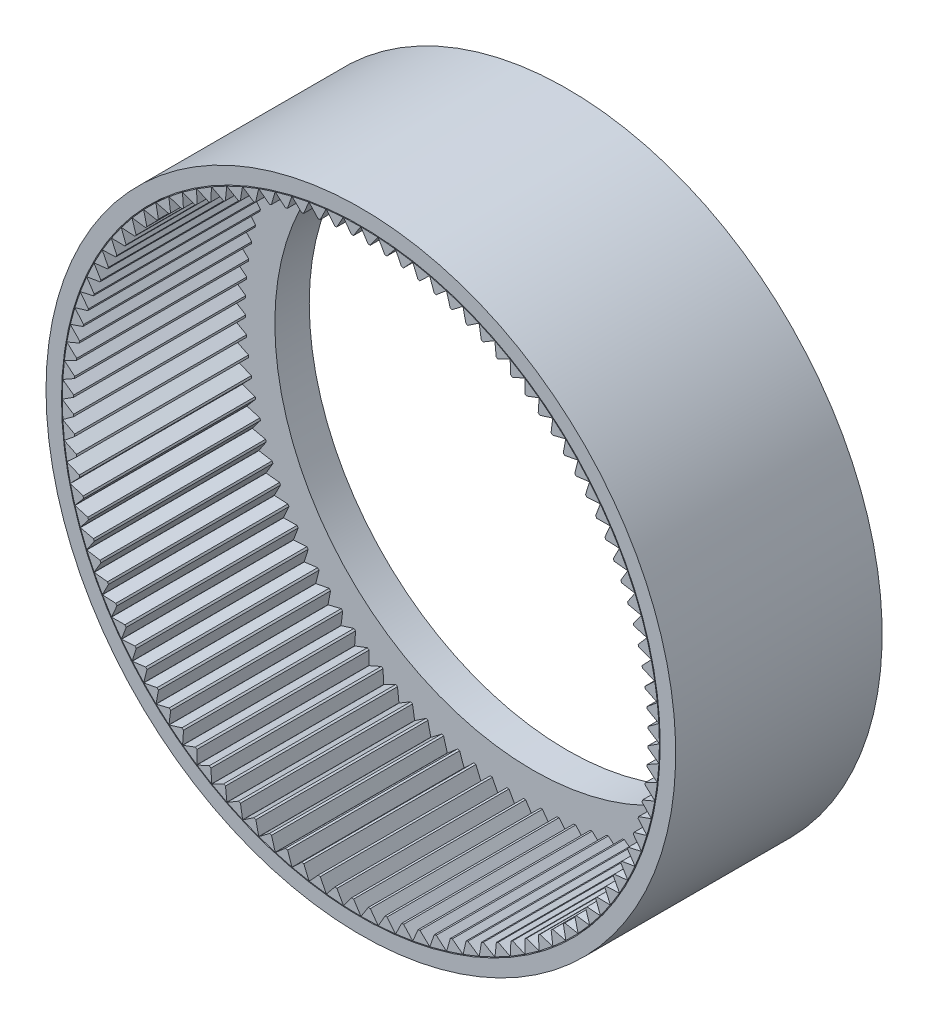
SolidWorks part; units mm, degrees
ref_plane "Alzado" through (0, 0, 0) normal (0, 0, 1) x (1, 0, 0)
ref_plane "Planta" through (0, 0, 0) normal (0, 1, 0) x (1, 0, 0)
ref_plane "Vista lateral" through (0, 0, 0) normal (1, 0, 0) x (0, 0, -1)
sketch "Croquis2" plane through (0, 0, 0) normal (0, 0, 1) x (1, 0, 0)
  line L0 (0, 8.6755) -> (0.2107, 8.3473)
  line L2 (0.5, 8.6611) -> (0.2707, 8.3456)
  line L4 (0.2107, 8.3473) -> (0.2707, 8.3456)
  line L5 (0, 8.6755) -> (0.5, 8.6611)
  line L6 (0.5044, 8.6608) -> (1.0028, 8.6174)
  line L7 (1.0028, 8.6174) -> (0.7555, 8.3158)
  line L8 (0.6957, 8.321) -> (0.7555, 8.3158)
  line L9 (0.5044, 8.6608) -> (0.6957, 8.321)
  line L10 (1.0072, 8.6169) -> (1.5021, 8.5445)
  line L11 (1.5021, 8.5445) -> (1.2378, 8.2578)
  line L12 (1.1784, 8.2664) -> (1.2378, 8.2578)
  line L13 (1.0072, 8.6169) -> (1.1784, 8.2664)
  line L14 (1.5065, 8.5437) -> (1.9964, 8.4427)
  line L15 (1.9964, 8.4427) -> (1.7158, 8.1718)
  line L16 (1.657, 8.1839) -> (1.7158, 8.1718)
  line L17 (1.5065, 8.5437) -> (1.657, 8.1839)
  line L18 (2.0007, 8.4417) -> (2.4839, 8.3123)
  line L19 (2.4839, 8.3123) -> (2.1881, 8.0582)
  line L20 (2.1301, 8.0737) -> (2.1881, 8.0582)
  line L21 (2.0007, 8.4417) -> (2.1301, 8.0737)
  line L22 (2.4882, 8.3111) -> (2.963, 8.1538)
  line L23 (2.963, 8.1538) -> (2.6529, 7.9174)
  line L24 (2.5959, 7.9362) -> (2.6529, 7.9174)
  line L25 (2.4882, 8.3111) -> (2.5959, 7.9362)
  line L26 (2.9672, 8.1523) -> (3.4321, 7.9678)
  line L27 (3.4321, 7.9678) -> (3.1088, 7.7497)
  line L28 (3.053, 7.7719) -> (3.1088, 7.7497)
  line L29 (2.9672, 8.1523) -> (3.053, 7.7719)
  line L30 (3.4362, 7.966) -> (3.8896, 7.7547)
  line L31 (3.8896, 7.7547) -> (3.5541, 7.5558)
  line L32 (3.4997, 7.5812) -> (3.5541, 7.5558)
  line L33 (3.4362, 7.966) -> (3.4997, 7.5812)
  line L34 (3.8936, 7.7527) -> (4.3339, 7.5154)
  line L35 (4.3339, 7.5154) -> (3.9874, 7.3364)
  line L36 (3.9346, 7.3649) -> (3.9874, 7.3364)
  line L37 (3.8936, 7.7527) -> (3.9346, 7.3649)
  line L38 (4.3378, 7.5132) -> (4.7636, 7.2507)
  line L39 (4.7636, 7.2507) -> (4.4073, 7.0922)
  line L40 (4.3562, 7.1237) -> (4.4073, 7.0922)
  line L41 (4.3378, 7.5132) -> (4.3562, 7.1237)
  line L42 (4.7673, 7.2483) -> (5.1771, 6.9615)
  line L43 (5.1771, 6.9615) -> (4.8122, 6.8239)
  line L44 (4.763, 6.8583) -> (4.8122, 6.8239)
  line L45 (4.7673, 7.2483) -> (4.763, 6.8583)
  line L46 (5.1807, 6.9588) -> (5.5731, 6.6487)
  line L47 (5.5731, 6.6487) -> (5.2008, 6.5325)
  line L48 (5.1537, 6.5698) -> (5.2008, 6.5325)
  line L49 (5.1807, 6.9588) -> (5.1537, 6.5698)
  line L50 (5.5765, 6.6458) -> (5.9503, 6.3134)
  line L51 (5.9503, 6.3134) -> (5.5718, 6.2191)
  line L52 (5.527, 6.259) -> (5.5718, 6.2191)
  line L53 (5.5765, 6.6458) -> (5.527, 6.259)
  line L54 (5.9535, 6.3103) -> (6.3073, 5.9567)
  line L55 (6.3073, 5.9567) -> (5.924, 5.8846)
  line L56 (5.8816, 5.927) -> (5.924, 5.8846)
  line L57 (5.9535, 6.3103) -> (5.8816, 5.927)
  line L58 (6.3103, 5.9535) -> (6.643, 5.5799)
  line L59 (6.643, 5.5799) -> (6.2562, 5.5302)
  line L60 (6.2162, 5.575) -> (6.2562, 5.5302)
  line L61 (6.3103, 5.9535) -> (6.2162, 5.575)
  line L62 (6.6458, 5.5765) -> (6.9562, 5.1842)
  line L63 (6.9562, 5.1842) -> (6.5671, 5.1571)
  line L64 (6.5299, 5.2041) -> (6.5671, 5.1571)
  line L65 (6.6458, 5.5765) -> (6.5299, 5.2041)
  line L66 (6.9588, 5.1807) -> (7.2458, 4.771)
  line L67 (7.2458, 4.771) -> (6.8559, 4.7665)
  line L68 (6.8214, 4.8157) -> (6.8559, 4.7665)
  line L69 (6.9588, 5.1807) -> (6.8214, 4.8157)
  line L70 (7.2483, 4.7673) -> (7.511, 4.3416)
  line L71 (7.511, 4.3416) -> (7.1214, 4.3598)
  line L72 (7.0899, 4.4109) -> (7.1214, 4.3598)
  line L73 (7.2483, 4.7673) -> (7.0899, 4.4109)
  line L74 (7.5132, 4.3378) -> (7.7507, 3.8975)
  line L75 (7.7507, 3.8975) -> (7.3629, 3.9384)
  line L76 (7.3344, 3.9912) -> (7.3629, 3.9384)
  line L77 (7.5132, 4.3378) -> (7.3344, 3.9912)
  line L78 (7.7527, 3.8936) -> (7.9642, 3.4403)
  line L79 (7.9642, 3.4403) -> (7.5794, 3.5036)
  line L80 (7.554, 3.558) -> (7.5794, 3.5036)
  line L81 (7.7527, 3.8936) -> (7.554, 3.558)
  line L82 (7.966, 3.4362) -> (8.1508, 2.9714)
  line L83 (8.1508, 2.9714) -> (7.7703, 3.0569)
  line L84 (7.7481, 3.1127) -> (7.7703, 3.0569)
  line L85 (7.966, 3.4362) -> (7.7481, 3.1127)
  line L86 (8.1523, 2.9672) -> (8.3098, 2.4924)
  line L87 (8.3098, 2.4924) -> (7.9349, 2.6)
  line L88 (7.916, 2.6569) -> (7.9349, 2.6)
  line L89 (8.1523, 2.9672) -> (7.916, 2.6569)
  line L90 (8.3111, 2.4882) -> (8.4406, 2.005)
  line L91 (8.4406, 2.005) -> (8.0727, 2.1342)
  line L92 (8.0571, 2.1922) -> (8.0727, 2.1342)
  line L93 (8.3111, 2.4882) -> (8.0571, 2.1922)
  line L94 (8.4417, 2.0007) -> (8.5429, 1.5109)
  line L95 (8.5429, 1.5109) -> (8.1831, 1.6612)
  line L96 (8.1709, 1.72) -> (8.1831, 1.6612)
  line L97 (8.4417, 2.0007) -> (8.1709, 1.72)
  line L98 (8.5437, 1.5065) -> (8.6163, 1.0116)
  line L99 (8.6163, 1.0116) -> (8.2658, 1.1826)
  line L100 (8.2571, 1.242) -> (8.2658, 1.1826)
  line L101 (8.5437, 1.5065) -> (8.2571, 1.242)
  line L102 (8.6169, 1.0072) -> (8.6606, 0.5089)
  line L103 (8.6606, 0.5089) -> (8.3206, 0.7)
  line L104 (8.3154, 0.7598) -> (8.3206, 0.7)
  line L105 (8.6169, 1.0072) -> (8.3154, 0.7598)
  line L106 (8.6608, 0.5044) -> (8.6755, 0.0044)
  line L107 (8.6755, 0.0044) -> (8.3472, 0.215)
  line L108 (8.3455, 0.275) -> (8.3472, 0.215)
  line L109 (8.6608, 0.5044) -> (8.3455, 0.275)
  line L110 (8.6755, 0) -> (8.6611, -0.5)
  line L111 (8.6611, -0.5) -> (8.3456, -0.2707)
  line L112 (8.3473, -0.2107) -> (8.3456, -0.2707)
  line L113 (8.6755, 0) -> (8.3473, -0.2107)
  line L114 (8.6608, -0.5044) -> (8.6174, -1.0028)
  line L115 (8.6174, -1.0028) -> (8.3158, -0.7555)
  line L116 (8.321, -0.6957) -> (8.3158, -0.7555)
  line L117 (8.6608, -0.5044) -> (8.321, -0.6957)
  line L118 (8.6169, -1.0072) -> (8.5445, -1.5021)
  line L119 (8.5445, -1.5021) -> (8.2578, -1.2378)
  line L120 (8.2664, -1.1784) -> (8.2578, -1.2378)
  line L121 (8.6169, -1.0072) -> (8.2664, -1.1784)
  line L122 (8.5437, -1.5065) -> (8.4427, -1.9964)
  line L123 (8.4427, -1.9964) -> (8.1718, -1.7158)
  line L124 (8.1839, -1.657) -> (8.1718, -1.7158)
  line L125 (8.5437, -1.5065) -> (8.1839, -1.657)
  line L126 (8.4417, -2.0007) -> (8.3123, -2.4839)
  line L127 (8.3123, -2.4839) -> (8.0582, -2.1881)
  line L128 (8.0737, -2.1301) -> (8.0582, -2.1881)
  line L129 (8.4417, -2.0007) -> (8.0737, -2.1301)
  line L130 (8.3111, -2.4882) -> (8.1538, -2.963)
  line L131 (8.1538, -2.963) -> (7.9174, -2.6529)
  line L132 (7.9362, -2.5959) -> (7.9174, -2.6529)
  line L133 (8.3111, -2.4882) -> (7.9362, -2.5959)
  line L134 (8.1523, -2.9672) -> (7.9678, -3.4321)
  line L135 (7.9678, -3.4321) -> (7.7497, -3.1088)
  line L136 (7.7719, -3.053) -> (7.7497, -3.1088)
  line L137 (8.1523, -2.9672) -> (7.7719, -3.053)
  line L138 (7.966, -3.4362) -> (7.7547, -3.8896)
  line L139 (7.7547, -3.8896) -> (7.5558, -3.5541)
  line L140 (7.5812, -3.4997) -> (7.5558, -3.5541)
  line L141 (7.966, -3.4362) -> (7.5812, -3.4997)
  line L142 (7.7527, -3.8936) -> (7.5154, -4.3339)
  line L143 (7.5154, -4.3339) -> (7.3364, -3.9874)
  line L144 (7.3649, -3.9346) -> (7.3364, -3.9874)
  line L145 (7.7527, -3.8936) -> (7.3649, -3.9346)
  line L146 (7.5132, -4.3378) -> (7.2507, -4.7636)
  line L147 (7.2507, -4.7636) -> (7.0922, -4.4073)
  line L148 (7.1237, -4.3562) -> (7.0922, -4.4073)
  line L149 (7.5132, -4.3378) -> (7.1237, -4.3562)
  line L150 (7.2483, -4.7673) -> (6.9615, -5.1771)
  line L151 (6.9615, -5.1771) -> (6.8239, -4.8122)
  line L152 (6.8583, -4.763) -> (6.8239, -4.8122)
  line L153 (7.2483, -4.7673) -> (6.8583, -4.763)
  line L154 (6.9588, -5.1807) -> (6.6487, -5.5731)
  line L155 (6.6487, -5.5731) -> (6.5325, -5.2008)
  line L156 (6.5698, -5.1537) -> (6.5325, -5.2008)
  line L157 (6.9588, -5.1807) -> (6.5698, -5.1537)
  line L158 (6.6458, -5.5765) -> (6.3134, -5.9503)
  line L159 (6.3134, -5.9503) -> (6.2191, -5.5718)
  line L160 (6.259, -5.527) -> (6.2191, -5.5718)
  line L161 (6.6458, -5.5765) -> (6.259, -5.527)
  line L162 (6.3103, -5.9535) -> (5.9567, -6.3073)
  line L163 (5.9567, -6.3073) -> (5.8846, -5.924)
  line L164 (5.927, -5.8816) -> (5.8846, -5.924)
  line L165 (6.3103, -5.9535) -> (5.927, -5.8816)
  line L166 (5.9535, -6.3103) -> (5.5799, -6.643)
  line L167 (5.5799, -6.643) -> (5.5302, -6.2562)
  line L168 (5.575, -6.2162) -> (5.5302, -6.2562)
  line L169 (5.9535, -6.3103) -> (5.575, -6.2162)
  line L170 (5.5765, -6.6458) -> (5.1842, -6.9562)
  line L171 (5.1842, -6.9562) -> (5.1571, -6.5671)
  line L172 (5.2041, -6.5299) -> (5.1571, -6.5671)
  line L173 (5.5765, -6.6458) -> (5.2041, -6.5299)
  line L174 (5.1807, -6.9588) -> (4.771, -7.2458)
  line L175 (4.771, -7.2458) -> (4.7665, -6.8559)
  line L176 (4.8157, -6.8214) -> (4.7665, -6.8559)
  line L177 (5.1807, -6.9588) -> (4.8157, -6.8214)
  line L178 (4.7673, -7.2483) -> (4.3416, -7.511)
  line L179 (4.3416, -7.511) -> (4.3598, -7.1214)
  line L180 (4.4109, -7.0899) -> (4.3598, -7.1214)
  line L181 (4.7673, -7.2483) -> (4.4109, -7.0899)
  line L182 (4.3378, -7.5132) -> (3.8975, -7.7507)
  line L183 (3.8975, -7.7507) -> (3.9384, -7.3629)
  line L184 (3.9912, -7.3344) -> (3.9384, -7.3629)
  line L185 (4.3378, -7.5132) -> (3.9912, -7.3344)
  line L186 (3.8936, -7.7527) -> (3.4403, -7.9642)
  line L187 (3.4403, -7.9642) -> (3.5036, -7.5794)
  line L188 (3.558, -7.554) -> (3.5036, -7.5794)
  line L189 (3.8936, -7.7527) -> (3.558, -7.554)
  line L190 (3.4362, -7.966) -> (2.9714, -8.1508)
  line L191 (2.9714, -8.1508) -> (3.0569, -7.7703)
  line L192 (3.1127, -7.7481) -> (3.0569, -7.7703)
  line L193 (3.4362, -7.966) -> (3.1127, -7.7481)
  line L194 (2.9672, -8.1523) -> (2.4924, -8.3098)
  line L195 (2.4924, -8.3098) -> (2.6, -7.9349)
  line L196 (2.6569, -7.916) -> (2.6, -7.9349)
  line L197 (2.9672, -8.1523) -> (2.6569, -7.916)
  line L198 (2.4882, -8.3111) -> (2.005, -8.4406)
  line L199 (2.005, -8.4406) -> (2.1342, -8.0727)
  line L200 (2.1922, -8.0571) -> (2.1342, -8.0727)
  line L201 (2.4882, -8.3111) -> (2.1922, -8.0571)
  line L202 (2.0007, -8.4417) -> (1.5109, -8.5429)
  line L203 (1.5109, -8.5429) -> (1.6612, -8.1831)
  line L204 (1.72, -8.1709) -> (1.6612, -8.1831)
  line L205 (2.0007, -8.4417) -> (1.72, -8.1709)
  line L206 (1.5065, -8.5437) -> (1.0116, -8.6163)
  line L207 (1.0116, -8.6163) -> (1.1826, -8.2658)
  line L208 (1.242, -8.2571) -> (1.1826, -8.2658)
  line L209 (1.5065, -8.5437) -> (1.242, -8.2571)
  line L210 (1.0072, -8.6169) -> (0.5089, -8.6606)
  line L211 (0.5089, -8.6606) -> (0.7, -8.3206)
  line L212 (0.7598, -8.3154) -> (0.7, -8.3206)
  line L213 (1.0072, -8.6169) -> (0.7598, -8.3154)
  line L214 (0.5044, -8.6608) -> (0.0044, -8.6755)
  line L215 (0.0044, -8.6755) -> (0.215, -8.3472)
  line L216 (0.275, -8.3455) -> (0.215, -8.3472)
  line L217 (0.5044, -8.6608) -> (0.275, -8.3455)
  line L218 (0, -8.6755) -> (-0.5, -8.6611)
  line L219 (-0.5, -8.6611) -> (-0.2707, -8.3456)
  line L220 (-0.2107, -8.3473) -> (-0.2707, -8.3456)
  line L221 (0, -8.6755) -> (-0.2107, -8.3473)
  line L222 (-0.5044, -8.6608) -> (-1.0028, -8.6174)
  line L223 (-1.0028, -8.6174) -> (-0.7555, -8.3158)
  line L224 (-0.6957, -8.321) -> (-0.7555, -8.3158)
  line L225 (-0.5044, -8.6608) -> (-0.6957, -8.321)
  line L226 (-1.0072, -8.6169) -> (-1.5021, -8.5445)
  line L227 (-1.5021, -8.5445) -> (-1.2378, -8.2578)
  line L228 (-1.1784, -8.2664) -> (-1.2378, -8.2578)
  line L229 (-1.0072, -8.6169) -> (-1.1784, -8.2664)
  line L230 (-1.5065, -8.5437) -> (-1.9964, -8.4427)
  line L231 (-1.9964, -8.4427) -> (-1.7158, -8.1718)
  line L232 (-1.657, -8.1839) -> (-1.7158, -8.1718)
  line L233 (-1.5065, -8.5437) -> (-1.657, -8.1839)
  line L234 (-2.0007, -8.4417) -> (-2.4839, -8.3123)
  line L235 (-2.4839, -8.3123) -> (-2.1881, -8.0582)
  line L236 (-2.1301, -8.0737) -> (-2.1881, -8.0582)
  line L237 (-2.0007, -8.4417) -> (-2.1301, -8.0737)
  line L238 (-2.4882, -8.3111) -> (-2.963, -8.1538)
  line L239 (-2.963, -8.1538) -> (-2.6529, -7.9174)
  line L240 (-2.5959, -7.9362) -> (-2.6529, -7.9174)
  line L241 (-2.4882, -8.3111) -> (-2.5959, -7.9362)
  line L242 (-2.9672, -8.1523) -> (-3.4321, -7.9678)
  line L243 (-3.4321, -7.9678) -> (-3.1088, -7.7497)
  line L244 (-3.053, -7.7719) -> (-3.1088, -7.7497)
  line L245 (-2.9672, -8.1523) -> (-3.053, -7.7719)
  line L246 (-3.4362, -7.966) -> (-3.8896, -7.7547)
  line L247 (-3.8896, -7.7547) -> (-3.5541, -7.5558)
  line L248 (-3.4997, -7.5812) -> (-3.5541, -7.5558)
  line L249 (-3.4362, -7.966) -> (-3.4997, -7.5812)
  line L250 (-3.8936, -7.7527) -> (-4.3339, -7.5154)
  line L251 (-4.3339, -7.5154) -> (-3.9874, -7.3364)
  line L252 (-3.9346, -7.3649) -> (-3.9874, -7.3364)
  line L253 (-3.8936, -7.7527) -> (-3.9346, -7.3649)
  line L254 (-4.3378, -7.5132) -> (-4.7636, -7.2507)
  line L255 (-4.7636, -7.2507) -> (-4.4073, -7.0922)
  line L256 (-4.3562, -7.1237) -> (-4.4073, -7.0922)
  line L257 (-4.3378, -7.5132) -> (-4.3562, -7.1237)
  line L258 (-4.7673, -7.2483) -> (-5.1771, -6.9615)
  line L259 (-5.1771, -6.9615) -> (-4.8122, -6.8239)
  line L260 (-4.763, -6.8583) -> (-4.8122, -6.8239)
  line L261 (-4.7673, -7.2483) -> (-4.763, -6.8583)
  line L262 (-5.1807, -6.9588) -> (-5.5731, -6.6487)
  line L263 (-5.5731, -6.6487) -> (-5.2008, -6.5325)
  line L264 (-5.1537, -6.5698) -> (-5.2008, -6.5325)
  line L265 (-5.1807, -6.9588) -> (-5.1537, -6.5698)
  line L266 (-5.5765, -6.6458) -> (-5.9503, -6.3134)
  line L267 (-5.9503, -6.3134) -> (-5.5718, -6.2191)
  line L268 (-5.527, -6.259) -> (-5.5718, -6.2191)
  line L269 (-5.5765, -6.6458) -> (-5.527, -6.259)
  line L270 (-5.9535, -6.3103) -> (-6.3073, -5.9567)
  line L271 (-6.3073, -5.9567) -> (-5.924, -5.8846)
  line L272 (-5.8816, -5.927) -> (-5.924, -5.8846)
  line L273 (-5.9535, -6.3103) -> (-5.8816, -5.927)
  line L274 (-6.3103, -5.9535) -> (-6.643, -5.5799)
  line L275 (-6.643, -5.5799) -> (-6.2562, -5.5302)
  line L276 (-6.2162, -5.575) -> (-6.2562, -5.5302)
  line L277 (-6.3103, -5.9535) -> (-6.2162, -5.575)
  line L278 (-6.6458, -5.5765) -> (-6.9562, -5.1842)
  line L279 (-6.9562, -5.1842) -> (-6.5671, -5.1571)
  line L280 (-6.5299, -5.2041) -> (-6.5671, -5.1571)
  line L281 (-6.6458, -5.5765) -> (-6.5299, -5.2041)
  line L282 (-6.9588, -5.1807) -> (-7.2458, -4.771)
  line L283 (-7.2458, -4.771) -> (-6.8559, -4.7665)
  line L284 (-6.8214, -4.8157) -> (-6.8559, -4.7665)
  line L285 (-6.9588, -5.1807) -> (-6.8214, -4.8157)
  line L286 (-7.2483, -4.7673) -> (-7.511, -4.3416)
  line L287 (-7.511, -4.3416) -> (-7.1214, -4.3598)
  line L288 (-7.0899, -4.4109) -> (-7.1214, -4.3598)
  line L289 (-7.2483, -4.7673) -> (-7.0899, -4.4109)
  line L290 (-7.5132, -4.3378) -> (-7.7507, -3.8975)
  line L291 (-7.7507, -3.8975) -> (-7.3629, -3.9384)
  line L292 (-7.3344, -3.9912) -> (-7.3629, -3.9384)
  line L293 (-7.5132, -4.3378) -> (-7.3344, -3.9912)
  line L294 (-7.7527, -3.8936) -> (-7.9642, -3.4403)
  line L295 (-7.9642, -3.4403) -> (-7.5794, -3.5036)
  line L296 (-7.554, -3.558) -> (-7.5794, -3.5036)
  line L297 (-7.7527, -3.8936) -> (-7.554, -3.558)
  line L298 (-7.966, -3.4362) -> (-8.1508, -2.9714)
  line L299 (-8.1508, -2.9714) -> (-7.7703, -3.0569)
  line L300 (-7.7481, -3.1127) -> (-7.7703, -3.0569)
  line L301 (-7.966, -3.4362) -> (-7.7481, -3.1127)
  line L302 (-8.1523, -2.9672) -> (-8.3098, -2.4924)
  line L303 (-8.3098, -2.4924) -> (-7.9349, -2.6)
  line L304 (-7.916, -2.6569) -> (-7.9349, -2.6)
  line L305 (-8.1523, -2.9672) -> (-7.916, -2.6569)
  line L306 (-8.3111, -2.4882) -> (-8.4406, -2.005)
  line L307 (-8.4406, -2.005) -> (-8.0727, -2.1342)
  line L308 (-8.0571, -2.1922) -> (-8.0727, -2.1342)
  line L309 (-8.3111, -2.4882) -> (-8.0571, -2.1922)
  line L310 (-8.4417, -2.0007) -> (-8.5429, -1.5109)
  line L311 (-8.5429, -1.5109) -> (-8.1831, -1.6612)
  line L312 (-8.1709, -1.72) -> (-8.1831, -1.6612)
  line L313 (-8.4417, -2.0007) -> (-8.1709, -1.72)
  line L314 (-8.5437, -1.5065) -> (-8.6163, -1.0116)
  line L315 (-8.6163, -1.0116) -> (-8.2658, -1.1826)
  line L316 (-8.2571, -1.242) -> (-8.2658, -1.1826)
  line L317 (-8.5437, -1.5065) -> (-8.2571, -1.242)
  line L318 (-8.6169, -1.0072) -> (-8.6606, -0.5089)
  line L319 (-8.6606, -0.5089) -> (-8.3206, -0.7)
  line L320 (-8.3154, -0.7598) -> (-8.3206, -0.7)
  line L321 (-8.6169, -1.0072) -> (-8.3154, -0.7598)
  line L322 (-8.6608, -0.5044) -> (-8.6755, -0.0044)
  line L323 (-8.6755, -0.0044) -> (-8.3472, -0.215)
  line L324 (-8.3455, -0.275) -> (-8.3472, -0.215)
  line L325 (-8.6608, -0.5044) -> (-8.3455, -0.275)
  line L326 (-8.6755, 0) -> (-8.6611, 0.5)
  line L327 (-8.6611, 0.5) -> (-8.3456, 0.2707)
  line L328 (-8.3473, 0.2107) -> (-8.3456, 0.2707)
  line L329 (-8.6755, 0) -> (-8.3473, 0.2107)
  line L330 (-8.6608, 0.5044) -> (-8.6174, 1.0028)
  line L331 (-8.6174, 1.0028) -> (-8.3158, 0.7555)
  line L332 (-8.321, 0.6957) -> (-8.3158, 0.7555)
  line L333 (-8.6608, 0.5044) -> (-8.321, 0.6957)
  line L334 (-8.6169, 1.0072) -> (-8.5445, 1.5021)
  line L335 (-8.5445, 1.5021) -> (-8.2578, 1.2378)
  line L336 (-8.2664, 1.1784) -> (-8.2578, 1.2378)
  line L337 (-8.6169, 1.0072) -> (-8.2664, 1.1784)
  line L338 (-8.5437, 1.5065) -> (-8.4427, 1.9964)
  line L339 (-8.4427, 1.9964) -> (-8.1718, 1.7158)
  line L340 (-8.1839, 1.657) -> (-8.1718, 1.7158)
  line L341 (-8.5437, 1.5065) -> (-8.1839, 1.657)
  line L342 (-8.4417, 2.0007) -> (-8.3123, 2.4839)
  line L343 (-8.3123, 2.4839) -> (-8.0582, 2.1881)
  line L344 (-8.0737, 2.1301) -> (-8.0582, 2.1881)
  line L345 (-8.4417, 2.0007) -> (-8.0737, 2.1301)
  line L346 (-8.3111, 2.4882) -> (-8.1538, 2.963)
  line L347 (-8.1538, 2.963) -> (-7.9174, 2.6529)
  line L348 (-7.9362, 2.5959) -> (-7.9174, 2.6529)
  line L349 (-8.3111, 2.4882) -> (-7.9362, 2.5959)
  line L350 (-8.1523, 2.9672) -> (-7.9678, 3.4321)
  line L351 (-7.9678, 3.4321) -> (-7.7497, 3.1088)
  line L352 (-7.7719, 3.053) -> (-7.7497, 3.1088)
  line L353 (-8.1523, 2.9672) -> (-7.7719, 3.053)
  line L354 (-7.966, 3.4362) -> (-7.7547, 3.8896)
  line L355 (-7.7547, 3.8896) -> (-7.5558, 3.5541)
  line L356 (-7.5812, 3.4997) -> (-7.5558, 3.5541)
  line L357 (-7.966, 3.4362) -> (-7.5812, 3.4997)
  line L358 (-7.7527, 3.8936) -> (-7.5154, 4.3339)
  line L359 (-7.5154, 4.3339) -> (-7.3364, 3.9874)
  line L360 (-7.3649, 3.9346) -> (-7.3364, 3.9874)
  line L361 (-7.7527, 3.8936) -> (-7.3649, 3.9346)
  line L362 (-7.5132, 4.3378) -> (-7.2507, 4.7636)
  line L363 (-7.2507, 4.7636) -> (-7.0922, 4.4073)
  line L364 (-7.1237, 4.3562) -> (-7.0922, 4.4073)
  line L365 (-7.5132, 4.3378) -> (-7.1237, 4.3562)
  line L366 (-7.2483, 4.7673) -> (-6.9615, 5.1771)
  line L367 (-6.9615, 5.1771) -> (-6.8239, 4.8122)
  line L368 (-6.8583, 4.763) -> (-6.8239, 4.8122)
  line L369 (-7.2483, 4.7673) -> (-6.8583, 4.763)
  line L370 (-6.9588, 5.1807) -> (-6.6487, 5.5731)
  line L371 (-6.6487, 5.5731) -> (-6.5325, 5.2008)
  line L372 (-6.5698, 5.1537) -> (-6.5325, 5.2008)
  line L373 (-6.9588, 5.1807) -> (-6.5698, 5.1537)
  line L374 (-6.6458, 5.5765) -> (-6.3134, 5.9503)
  line L375 (-6.3134, 5.9503) -> (-6.2191, 5.5718)
  line L376 (-6.259, 5.527) -> (-6.2191, 5.5718)
  line L377 (-6.6458, 5.5765) -> (-6.259, 5.527)
  line L378 (-6.3103, 5.9535) -> (-5.9567, 6.3073)
  line L379 (-5.9567, 6.3073) -> (-5.8846, 5.924)
  line L380 (-5.927, 5.8816) -> (-5.8846, 5.924)
  line L381 (-6.3103, 5.9535) -> (-5.927, 5.8816)
  line L382 (-5.9535, 6.3103) -> (-5.5799, 6.643)
  line L383 (-5.5799, 6.643) -> (-5.5302, 6.2562)
  line L384 (-5.575, 6.2162) -> (-5.5302, 6.2562)
  line L385 (-5.9535, 6.3103) -> (-5.575, 6.2162)
  line L386 (-5.5765, 6.6458) -> (-5.1842, 6.9562)
  line L387 (-5.1842, 6.9562) -> (-5.1571, 6.5671)
  line L388 (-5.2041, 6.5299) -> (-5.1571, 6.5671)
  line L389 (-5.5765, 6.6458) -> (-5.2041, 6.5299)
  line L390 (-5.1807, 6.9588) -> (-4.771, 7.2458)
  line L391 (-4.771, 7.2458) -> (-4.7665, 6.8559)
  line L392 (-4.8157, 6.8214) -> (-4.7665, 6.8559)
  line L393 (-5.1807, 6.9588) -> (-4.8157, 6.8214)
  line L394 (-4.7673, 7.2483) -> (-4.3416, 7.511)
  line L395 (-4.3416, 7.511) -> (-4.3598, 7.1214)
  line L396 (-4.4109, 7.0899) -> (-4.3598, 7.1214)
  line L397 (-4.7673, 7.2483) -> (-4.4109, 7.0899)
  line L398 (-4.3378, 7.5132) -> (-3.8975, 7.7507)
  line L399 (-3.8975, 7.7507) -> (-3.9384, 7.3629)
  line L400 (-3.9912, 7.3344) -> (-3.9384, 7.3629)
  line L401 (-4.3378, 7.5132) -> (-3.9912, 7.3344)
  line L402 (-3.8936, 7.7527) -> (-3.4403, 7.9642)
  line L403 (-3.4403, 7.9642) -> (-3.5036, 7.5794)
  line L404 (-3.558, 7.554) -> (-3.5036, 7.5794)
  line L405 (-3.8936, 7.7527) -> (-3.558, 7.554)
  line L406 (-3.4362, 7.966) -> (-2.9714, 8.1508)
  line L407 (-2.9714, 8.1508) -> (-3.0569, 7.7703)
  line L408 (-3.1127, 7.7481) -> (-3.0569, 7.7703)
  line L409 (-3.4362, 7.966) -> (-3.1127, 7.7481)
  line L410 (-2.9672, 8.1523) -> (-2.4924, 8.3098)
  line L411 (-2.4924, 8.3098) -> (-2.6, 7.9349)
  line L412 (-2.6569, 7.916) -> (-2.6, 7.9349)
  line L413 (-2.9672, 8.1523) -> (-2.6569, 7.916)
  line L414 (-2.4882, 8.3111) -> (-2.005, 8.4406)
  line L415 (-2.005, 8.4406) -> (-2.1342, 8.0727)
  line L416 (-2.1922, 8.0571) -> (-2.1342, 8.0727)
  line L417 (-2.4882, 8.3111) -> (-2.1922, 8.0571)
  line L418 (-2.0007, 8.4417) -> (-1.5109, 8.5429)
  line L419 (-1.5109, 8.5429) -> (-1.6612, 8.1831)
  line L420 (-1.72, 8.1709) -> (-1.6612, 8.1831)
  line L421 (-2.0007, 8.4417) -> (-1.72, 8.1709)
  line L422 (-1.5065, 8.5437) -> (-1.0116, 8.6163)
  line L423 (-1.0116, 8.6163) -> (-1.1826, 8.2658)
  line L424 (-1.242, 8.2571) -> (-1.1826, 8.2658)
  line L425 (-1.5065, 8.5437) -> (-1.242, 8.2571)
  line L426 (-1.0072, 8.6169) -> (-0.5089, 8.6606)
  line L427 (-0.5089, 8.6606) -> (-0.7, 8.3206)
  line L428 (-0.7598, 8.3154) -> (-0.7, 8.3206)
  line L429 (-1.0072, 8.6169) -> (-0.7598, 8.3154)
  line L430 (-0.5044, 8.6608) -> (-0.0044, 8.6755)
  line L431 (-0.0044, 8.6755) -> (-0.215, 8.3472)
  line L432 (-0.275, 8.3455) -> (-0.215, 8.3472)
  line L433 (-0.5044, 8.6608) -> (-0.275, 8.3455)
  point P436 (0, 0)
  dimension "D2" = 0.5
  dimension "D4" = 0.39
  dimension "D3" = 0.06
  dimension "D5" = 0.39
extrude "Saliente-Extruir1" add sketch "Croquis2" along normal blind 5
sketch "Croquis3" plane through (0, 0, 0) normal (0, 0, -1) x (-1, 0, 0)
  circle A0 centre (0, 0) radius 9.15
  circle A1 centre (0, 0) radius 8.7
extrude "Saliente-Extruir2" add sketch "Croquis3" against normal blind 5 separate body
sketch "Croquis4" plane through (0, 0, 0) normal (0, 0, -1) x (-1, 0, 0)
  circle A0 centre (0, 0) radius 9.15
  circle A2 centre (0, 0) radius 7.5
extrude "Saliente-Extruir5" add sketch "Croquis4" along normal blind 1
